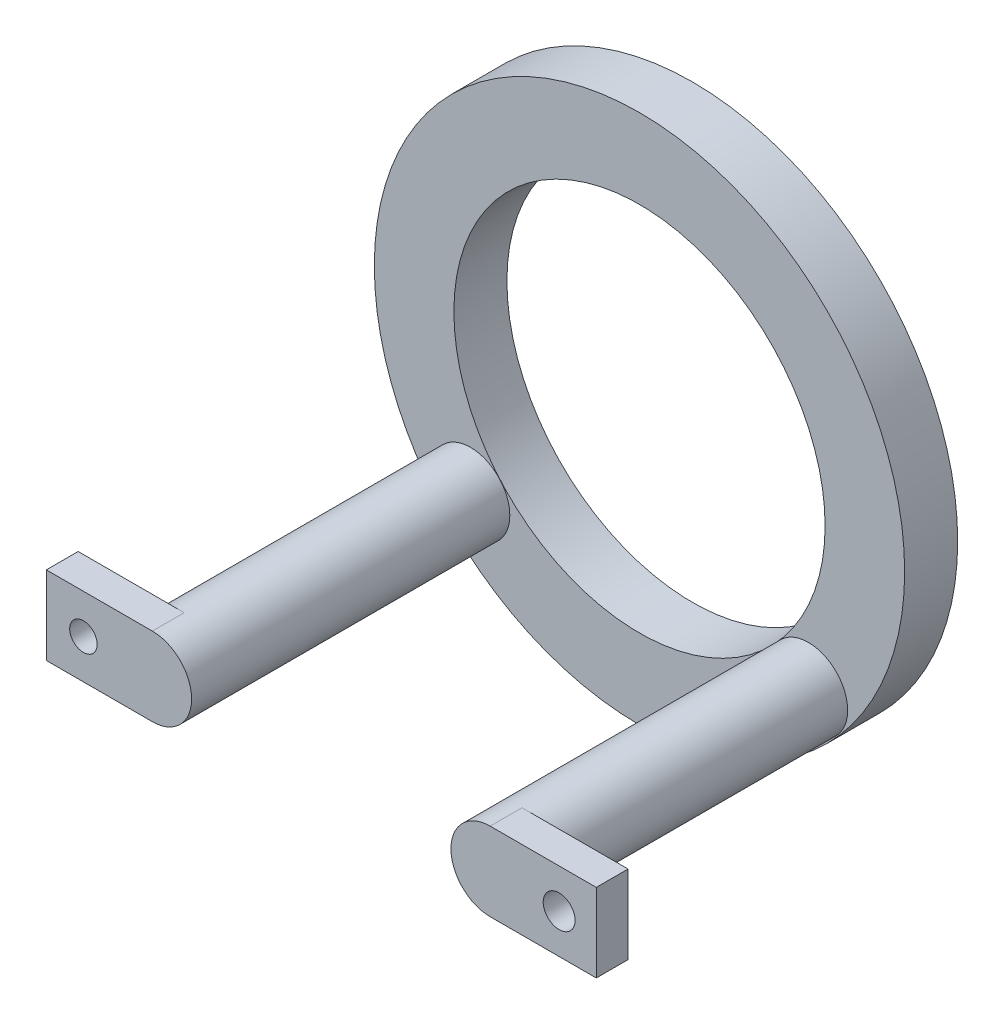
SolidWorks part; units mm, degrees
ref_plane "Plan de face" through (0, 0, 0) normal (0, 0, 1) x (1, 0, 0)
ref_plane "Plan de dessus" through (0, 0, 0) normal (0, 1, 0) x (1, 0, 0)
ref_plane "Plan de droite" through (0, 0, 0) normal (1, 0, 0) x (0, 0, -1)
sketch "Esquisse1" plane through (0, 0, 0) normal (0, 0, 1) x (1, 0, 0)
  circle A0 centre (0, 0) radius 35
  circle A1 centre (0, 0) radius 50
  dimension "D1" = 70
  dimension "D2" = 100
extrude "Boss.-Extru.2" add sketch "Esquisse1" along normal blind 10
sketch "Esquisse4" plane through (0, 0, 0) normal (0, 0, 1) x (1, 0, 0)
  circle A0 centre (-42.5, 0) radius 7.5
  circle A1 centre (42.5, 0) radius 7.5
  circle A2 centre (-31.85, -28) radius 7.4
  circle A3 centre (31.85, -28) radius 7.4
  point P9 (0, 0)
  dimension "D1" = 15
  dimension "D2" = 15
  dimension "D7" = 14.8
  dimension "D8" = 14.8
  dimension "D3" = 42.5
  dimension "D4" = 42.5
  dimension "D5" = 28
  dimension "D6" = 28
  dimension "D9" = 31.85
  dimension "D10" = 31.85
extrude "Boss.-Extru.3" add sketch "Esquisse4" along normal blind 70 contours A2 | A3
sketch "Esquisse5" plane through (0, 0, 70) normal (0, 0, 1) x (1, 0, 0)
  line L1 (-31.85, -20.6) -> (-51.85, -20.6)
  line L2 (-31.85, -20.6) -> (-31.85, -35.4)
  line L3 (-31.85, -35.4) -> (-51.85, -35.4)
  line L4 (-51.85, -20.6) -> (-51.85, -35.4)
  line L5 (31.85, -20.6) -> (51.85, -20.6)
  line L6 (31.85, -20.6) -> (31.85, -35.4)
  line L7 (31.85, -35.4) -> (51.85, -35.4)
  line L8 (51.85, -20.6) -> (51.85, -35.4)
  circle A0 centre (-31.85, -28) radius 7.4 construction
  circle A1 centre (-31.85, -28) radius 7.4 construction
  circle A2 centre (31.85, -28) radius 7.4 construction
  circle A3 centre (31.85, -28) radius 7.4 construction
  circle A4 centre (-44.85, -28) radius 2.5881
  circle A5 centre (44.85, -28) radius 3.0037
  dimension "D1" = 14.8
  dimension "D2" = 14.8
  dimension "D3" = 20
  dimension "D4" = 20
  dimension "D5" = 7
  dimension "D6" = 7
  dimension "D7" = 7.4
  dimension "D8" = 7.4
extrude "Boss.-Extru.4" add sketch "Esquisse5" against normal blind 6
